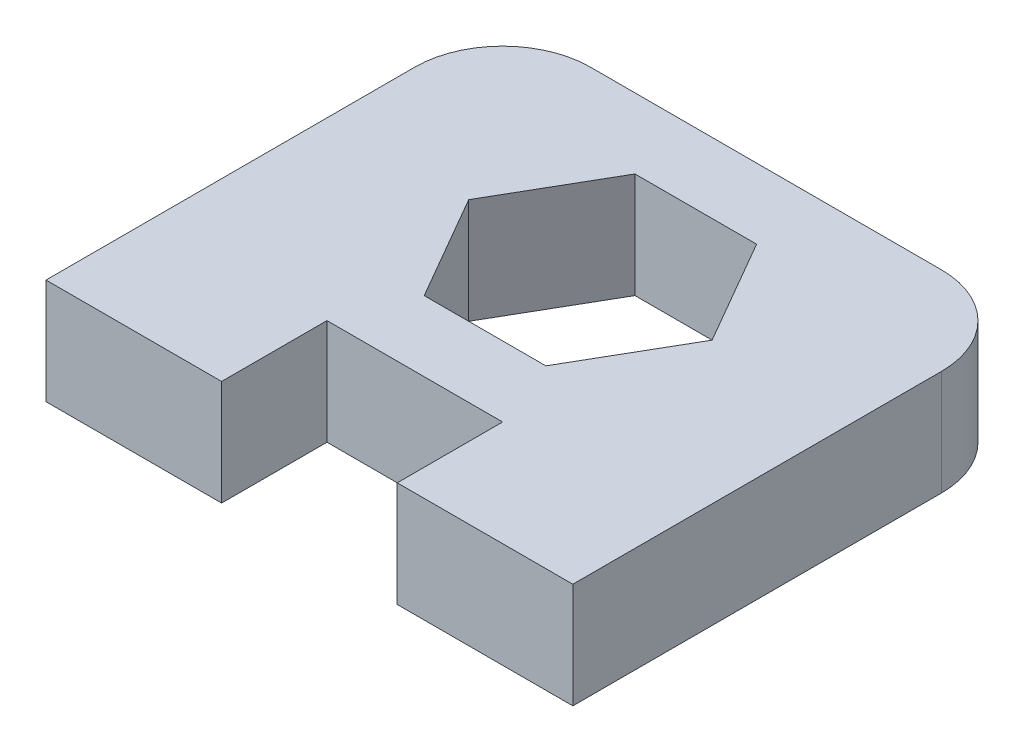
SolidWorks part; units mm, degrees
ref_plane "Front Plane" through (0, 0, 0) normal (0, 0, 1) x (1, 0, 0)
ref_plane "Top Plane" through (0, 0, 0) normal (0, 1, 0) x (1, 0, 0)
ref_plane "Right Plane" through (0, 0, 0) normal (1, 0, 0) x (0, 0, -1)
sketch "Sketch1" plane through (0, 0, 0) normal (0, 1, 0) x (1, 0, 0)
  line L0 (0, 0) -> (0, 10.5)
  line L1 (2.5, 13) -> (12.5, 13)
  line L2 (15, 10.5) -> (15, 0)
  line L3 (15, 0) -> (10, 0)
  line L4 (10, 0) -> (10, 3)
  line L5 (10, 3) -> (5, 3)
  line L6 (5, 3) -> (5, 0)
  line L7 (5, 0) -> (0, 0)
  line L9 (5.7679, 5) -> (9.2321, 5)
  line L10 (9.2321, 5) -> (10.9641, 8)
  line L11 (10.9641, 8) -> (9.2321, 11)
  line L12 (9.2321, 11) -> (5.7679, 11)
  line L13 (5.7679, 11) -> (4.0359, 8)
  line L14 (4.0359, 8) -> (5.7679, 5)
  circle A0 centre (7.5, 8) radius 3 construction
  arc A1 (12.5, 13) -> (15, 10.5) centre (12.5, 10.5) cw
  arc A2 (0, 10.5) -> (2.5, 13) centre (2.5, 10.5) cw
  point P10 (4.184, 9.0021)
  dimension "D5" = 6
  dimension "D6" = 7.5
  dimension "D7" = 5
  dimension "D8" = 2.5
  dimension "D1" = 5
  dimension "D2" = 3
  dimension "D3" = 5
  dimension "D4" = 10
extrude "Boss-Extrude1" add sketch "Sketch1" along normal blind 3
